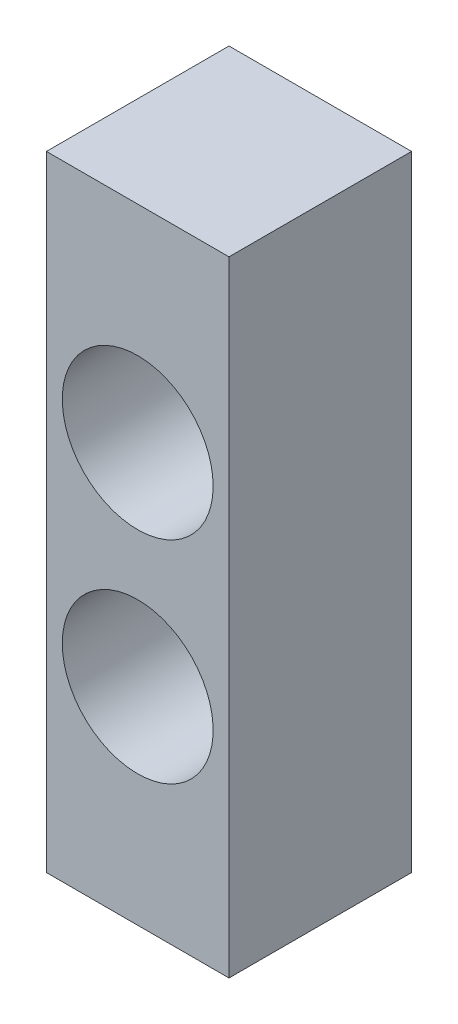
SolidWorks part; units mm, degrees
ref_plane "Front Plane" through (0, 0, 0) normal (0, 0, 1) x (1, 0, 0)
ref_plane "Top Plane" through (0, 0, 0) normal (0, 1, 0) x (1, 0, 0)
ref_plane "Right Plane" through (0, 0, 0) normal (1, 0, 0) x (0, 0, -1)
sketch "Sketch1" plane through (0, 0, 0) normal (0, 1, 0) x (1, 0, 0)
  line L0 (-4.826, 4.826) -> (4.826, -4.826) construction
  line L1 (-4.826, 4.826) -> (4.826, 4.826)
  line L2 (-4.826, 4.826) -> (-4.826, -4.826)
  line L3 (-4.826, -4.826) -> (4.826, -4.826)
  line L4 (4.826, 4.826) -> (4.826, -4.826)
  dimension "D1" = 9.652
  dimension "D2" = 9.652
extrude "Boss-Extrude1" add sketch "Sketch1" along normal blind 33.02
sketch "Sketch2" plane through (0, 0, 4.826) normal (0, 0, 1) x (1, 0, 0)
  line L0 (-4.826, 16.51) -> (4.826, 16.51) construction
  line L1 (-4.826, 33.02) -> (-4.826, 0) construction
  line L2 (4.826, 33.02) -> (4.826, 0) construction
  line L3 (0, 33.02) -> (0, 0) construction
  line L4 (-4.826, 33.02) -> (4.826, 33.02) construction
  circle A0 centre (0, 22.098) radius 3.9878
  circle A1 centre (0, 10.922) radius 3.9878
  dimension "D2" = 7.9756
  dimension "D1" = 11.176
extrude "Cut-Extrude1" cut sketch "Sketch2" against normal through all
